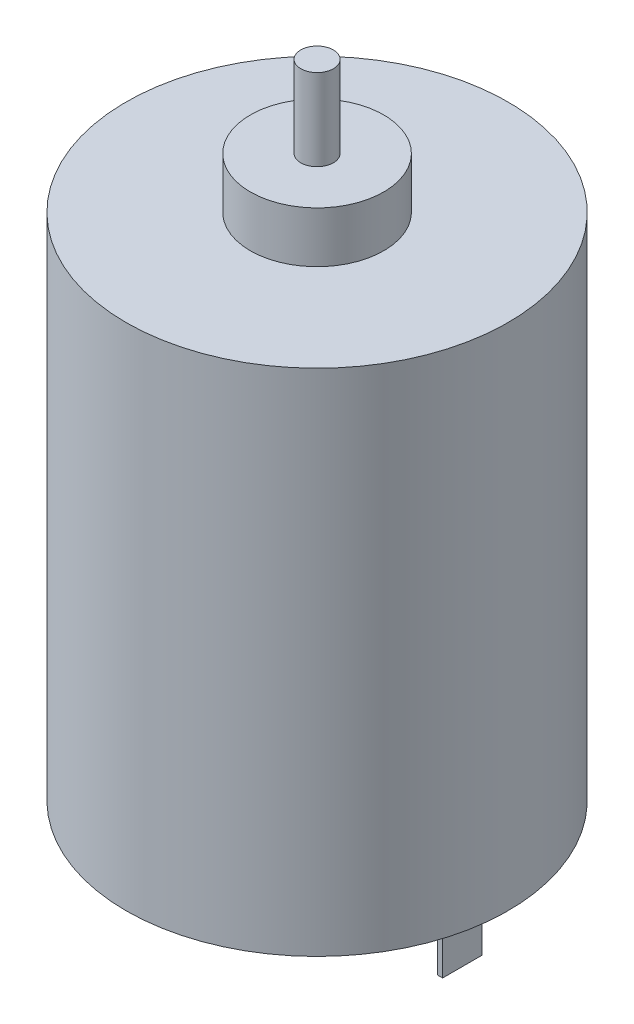
SolidWorks part; units mm, degrees
ref_plane "Front Plane" through (0, 0, 0) normal (0, 0, 1) x (1, 0, 0)
ref_plane "Top Plane" through (0, 0, 0) normal (0, 1, 0) x (1, 0, 0)
ref_plane "Right Plane" through (0, 0, 0) normal (1, 0, 0) x (0, 0, -1)
sketch "Sketch1" plane through (0, 0, 0) normal (0, 1, 0) x (1, 0, 0)
  circle A0 centre (0, 0) radius 18.75
  dimension "D1" = 37.5
extrude "Boss-Extrude1" add sketch "Sketch1" along normal blind 50
sketch "Sketch2" plane through (0, 50, 0) normal (0, 1, 0) x (1, 0, 0)
  circle A0 centre (0, 0) radius 6.55
  dimension "D1" = 13.1
extrude "Boss-Extrude2" add sketch "Sketch2" along normal blind 5
sketch "Sketch3" plane through (0, 55, 0) normal (0, 1, 0) x (1, 0, 0)
  circle A0 centre (0, 0) radius 1.6
  dimension "D1" = 3.2
extrude "Boss-Extrude3" add sketch "Sketch3" along normal blind 8
sketch "Sketch4" plane through (0, 0, 0) normal (0, -1, 0) x (1, 0, 0)
  circle A0 centre (0, 0) radius 6.5
  dimension "D1" = 13
extrude "Boss-Extrude4" add sketch "Sketch4" along normal blind 2.5
sketch "Sketch5" plane through (0, -2.5, 0) normal (0, -1, 0) x (1, 0, 0)
  circle A0 centre (0, 0) radius 4
  dimension "D1" = 8
extrude "Boss-Extrude5" add sketch "Sketch5" along normal blind 1.3
sketch "Sketch6" plane through (0, 0, 0) normal (0, -1, 0) x (1, 0, 0)
  line L1 (-13.75, -1.925) -> (-14.25, -1.925)
  line L2 (-13.75, -1.925) -> (-13.75, 1.925)
  line L3 (-13.75, 1.925) -> (-14.25, 1.925)
  line L4 (-14.25, -1.925) -> (-14.25, 1.925)
  line L5 (-13.75, -1.925) -> (-14.25, 1.925) construction
  line L6 (-13.75, 1.925) -> (-14.25, -1.925) construction
  line L7 (14.25, -1.925) -> (13.75, -1.925)
  line L8 (14.25, -1.925) -> (14.25, 1.925)
  line L9 (14.25, 1.925) -> (13.75, 1.925)
  line L10 (13.75, -1.925) -> (13.75, 1.925)
  line L11 (14.25, -1.925) -> (13.75, 1.925) construction
  line L12 (14.25, 1.925) -> (13.75, -1.925) construction
  point P0 (-14, 0)
  point P5 (14, 0)
  dimension "D1" = 0
  dimension "D2" = 14
  dimension "D3" = 14
  dimension "D4" = 3.85
  dimension "D5" = 3.85
  dimension "D6" = 0.5
  dimension "D7" = 0.5
extrude "Boss-Extrude6" add sketch "Sketch6" along normal blind 7
